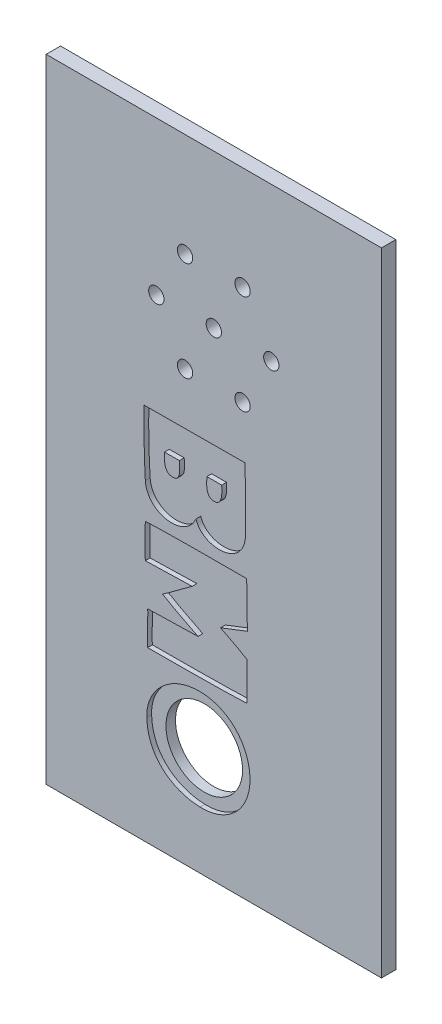
SolidWorks part; units mm, degrees
ref_plane "Front Plane" through (0, 0, 0) normal (0, 0, 1) x (1, 0, 0)
ref_plane "Top Plane" through (0, 0, 0) normal (0, 1, 0) x (1, 0, 0)
ref_plane "Right Plane" through (0, 0, 0) normal (1, 0, 0) x (0, 0, -1)
sketch "Sketch1" plane through (0, 0, 0) normal (0, 0, 1) x (1, 0, 0)
  line L1 (-35, -66) -> (35, -66)
  line L2 (-35, -66) -> (-35, 66)
  line L3 (-35, 66) -> (35, 66)
  line L4 (35, -66) -> (35, 66)
  line L5 (-35, -66) -> (35, 66) construction
  line L6 (-35, 66) -> (35, -66) construction
  point P0 (0, 0)
  dimension "D1" = 70
  dimension "D2" = 132
extrude "Boss-Extrude1" add sketch "Sketch1" along normal blind 3
sketch "Sketch2" plane through (0, 0, 3) normal (0, 0, 1) x (1, 0, 0)
  line L0 (35, 66) -> (-35, 66) construction
  line L1 (35, -66) -> (35, 66) construction
  line L2 (35, 66) -> (-35, 66) construction
  line L4 (-35, -66) -> (-35, 66) construction
  circle A0 centre (0, 34) radius 1.6
  circle A1 centre (12, 34) radius 1.6
  circle A2 centre (6, 23.6077) radius 1.6
  circle A3 centre (-6, 23.6077) radius 1.6
  circle A4 centre (-12, 34) radius 1.6
  circle A5 centre (-6, 44.3923) radius 1.6
  circle A6 centre (6, 44.3923) radius 1.6
  circle A7 centre (-3, -43.8976) radius 8
  point P2 (0, 66)
  point P24 (0, 34)
  dimension "D1" = 3.2
  dimension "D6" = 3.2
  dimension "D11" = 16
  dimension "D12" = 32
  dimension "D2" = 32
  dimension "D3" = 35
  dimension "D4" = 12
  dimension "D5" = 32
  dimension "D8" = 12
  dimension "D9" = 12
  dimension "D10" = 44
  dimension "D7" = 6
extrude "Cut-Extrude1" cut sketch "Sketch2" against normal through all
sketch "Sketch4" plane through (0, 0, 3) normal (0, 0, 1) x (1, 0, 0)
  line L0 (6.4585, 12.9067) -> (-14.5682, 12.7905)
  line L1 (-10.3034, 6.4259) -> (-7.1836, 6.4556)
  line L2 (-1.4556, 6.4386) -> (1.6426, 6.4377)
  spline S0 degree 3 poles (-2.6101, -33.1601) (3.4409, -33.3928) (7.4682, -38.0575) (7.5527, -43.7482) (7.6371, -49.4416) (3.1661, -54.2627) (-2.8848, -54.03) knots 2 2 2 2 3 3 3 4 4 4 4
  spline S1 degree 3 poles (-13.9952, -43.2933) (-14.11, -37.5976) (-8.6638, -32.9274) (-2.6101, -33.1601) knots 1 1 1 1 2 2 2 2
  spline S2 degree 3 poles (-2.8848, -54.03) (-8.9386, -53.7945) (-13.8602, -49.9783) (-13.9952, -43.2933) knots 0 0 0 0 1 1 1 1
  spline S3 degree 3 poles (-14.2919, -8.0629) (-10.383, -7.8974) (2.0912, -7.8226) (6.8631, -7.8621) knots 11 11 11 11 12 12 12 12
  spline S4 degree 3 poles (-14.3099, -15.2105) (-14.3327, -13.67) (-14.4028, -8.9466) (-14.2919, -8.0629) knots 10 10 10 10 11 11 11 11
  spline S5 degree 3 poles (-4.5285, -14.9524) (-9.1759, -15.1343) (-13.2076, -15.1941) (-14.3099, -15.2105) knots 9 9 9 9 10 10 10 10
  spline S6 degree 3 poles (-10.6997, -19.4348) (-8.6414, -18.0895) (-5.6211, -15.6274) (-4.5285, -14.9524) knots 8 8 8 8 9 9 9 9
  spline S7 degree 3 poles (-3.3035, -23.3935) (-6.7523, -21.6861) (-9.7144, -20.0818) (-10.6997, -19.4348) knots 7 7 7 7 8 8 8 8
  spline S8 degree 3 poles (-13.818, -23.6543) (-10.7618, -23.6089) (-4.8936, -23.4171) (-3.3035, -23.3935) knots 6 6 6 6 7 7 7 7
  spline S9 degree 3 poles (-13.8349, -30.6888) (-13.9871, -28.6072) (-13.682, -24.6473) (-13.818, -23.6543) knots 5 5 5 5 6 6 6 6
  spline S10 degree 3 poles (6.9491, -30.3804) (1.8184, -30.6771) (-12.3661, -30.667) (-13.8349, -30.6888) knots 4 4 4 4 5 5 5 5
  spline S11 degree 3 poles (6.9586, -22.4722) (7.001, -25.33) (6.9329, -29.2836) (6.9491, -30.3804) knots 3 3 3 3 4 4 4 4
  spline S12 degree 3 poles (1.4069, -19.4785) (3.1313, -20.3322) (6.3376, -22.0459) (6.9586, -22.4722) knots 2 2 2 2 3 3 3 3
  spline S13 degree 3 poles (7.0033, -17.3116) (5.7862, -17.7652) (2.1378, -19.1369) (1.4069, -19.4785) knots 1 1 1 1 2 2 2 2
  spline S14 degree 3 poles (6.8631, -7.8621) (6.8844, -9.2951) (6.9821, -15.8814) (7.0033, -17.3116) knots 0 0 0 0 1 1 1 1
  spline S15 degree 3 poles (-3.7148, -2.3574) (-2.3293, -6.9373) (6.3518, -6.6541) (6.6004, -0.3714) knots 0 0 0 0 1 1 1 1
  spline S16 degree 3 poles (6.6004, -0.3714) (6.6804, 1.6695) (6.6772, 9.685) (6.4585, 12.9067) knots 1 1 1 1 2 2 2 2
  spline S17 degree 3 poles (-14.5682, 12.7905) (-14.6811, 8.8858) (-14.4795, 1.7938) (-14.3019, -0.7008) knots 3 3 3 3 4 4 4 4
  spline S18 degree 3 poles (-14.3019, -0.7008) (-13.9047, -6.2931) (-6.0284, -7.4938) (-3.7148, -2.3574) knots 4 4 4 4 5 5 5 5
  spline S19 degree 3 poles (-7.1836, 6.4556) (-7.0509, 4.5722) (-6.9921, 2.8421) (-8.3968, 2.7661) knots 1 1 1 1 2 2 2 2
  spline S20 degree 3 poles (-8.3968, 2.7661) (-9.9501, 2.6824) (-10.4706, 3.9482) (-10.3034, 6.4259) knots 2 2 2 2 3 3 3 3
  spline S21 degree 3 poles (1.6426, 6.4377) (1.778, 4.5571) (1.6141, 2.7879) (0.2095, 2.7119) knots 1 1 1 1 2 2 2 2
  spline S22 degree 3 poles (0.2095, 2.7119) (-1.3412, 2.631) (-1.6256, 3.9636) (-1.4556, 6.4386) knots 2 2 2 2 3 3 3 3
extrude "Cut-Extrude4" cut sketch "Sketch4" against normal blind 1
